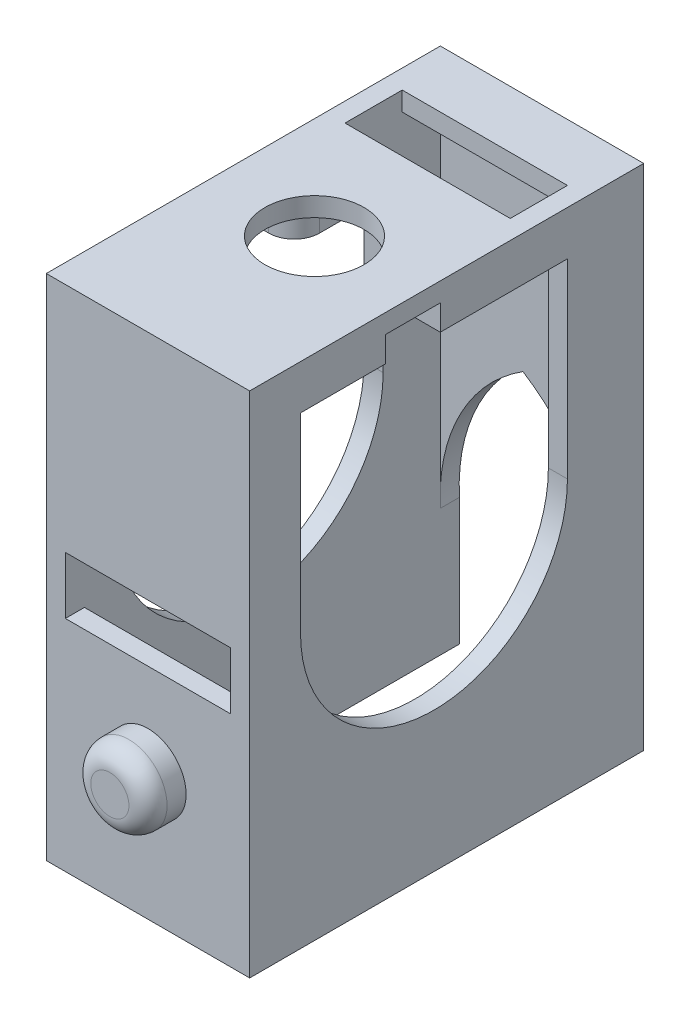
SolidWorks part; units mm, degrees
ref_plane "Front Plane" through (0, 0, 0) normal (0, 0, 1) x (1, 0, 0)
ref_plane "Top Plane" through (0, 0, 0) normal (0, 1, 0) x (1, 0, 0)
ref_plane "Right Plane" through (0, 0, 0) normal (1, 0, 0) x (0, 0, -1)
sketch "Sketch1" plane through (0, 0, 0) normal (0, 1, 0) x (1, 0, 0)
  line L1 (0, 0) -> (16, 0)
  line L2 (0, 0) -> (0, -31)
  line L3 (0, -31) -> (16, -31)
  line L4 (16, 0) -> (16, -31)
  dimension "D1" = 16
  dimension "D2" = 31
extrude "Boss-Extrude1" add sketch "Sketch1" along normal blind 40
shell "Shell1" thickness 1.5
sketch "Sketch2" plane through (0, 40, 0) normal (0, 1, 0) x (1, 0, 0)
  line L0 (16, 0) -> (0, 0) construction
  line L1 (1.5, -4.5) -> (14.5, -4.5)
  line L2 (1.5, -4.5) -> (1.5, -9)
  line L3 (1.5, -9) -> (14.5, -9)
  line L4 (14.5, -4.5) -> (14.5, -9)
  line L5 (16, -31) -> (16, 0) construction
  dimension "D1" = 13
  dimension "D2" = 4.5
  dimension "D3" = 4.5
  dimension "D4" = 1.5
extrude "Cut-Extrude1" cut sketch "Sketch2" against normal up to vertex (1.5 mm away)
sketch "Sketch3" plane through (0, 0, 0) normal (0, 0, -1) x (-1, 0, 0)
  line L0 (-16, 0) -> (0, 0) construction
  line L2 (-14.5, 10) -> (-14.5, -1)
  line L3 (-14.5, -1) -> (-1.5, -1)
  line L4 (-1.5, 10) -> (-1.5, -1)
  line L5 (-8, 10) -> (-8, 23.3795) construction
  line L6 (0, 40) -> (0, 0) construction
  arc A0 (-14.5, 10) -> (-8, 22.5665) centre (-0.5119, 10.729) cw
  arc A1 (-1.5, 10) -> (-8, 22.5665) centre (-15.4881, 10.729) ccw
  dimension "D4" = 1.5
  dimension "D1" = 13
  dimension "D2" = 1
  dimension "D3" = 11
extrude "Cut-Extrude2" cut sketch "Sketch3" against normal up to vertex (1.5 mm away)
sketch "Sketch4" plane through (0, 40, 0) normal (0, 1, 0) x (1, 0, 0)
  line L0 (1.5, -9) -> (14.5, -9) construction
  line L1 (16, -31) -> (16, 0) construction
  circle A0 centre (8, -17.9) radius 3.9
  dimension "D1" = 7.8
  dimension "D2" = 8.9
  dimension "D3" = 8
extrude "Cut-Extrude3" cut sketch "Sketch4" against normal up to vertex (1.5 mm away)
sketch "Sketch6" plane through (0, 38.5, 0) normal (0, -1, 0) x (-1, 0, 0)
  line L1 (-11.5, -9) -> (-14.5, -9)
  line L2 (-11.5, -9) -> (-11.5, -16)
  line L3 (-11.5, -16) -> (-14.5, -16)
  line L4 (-14.5, -9) -> (-14.5, -16)
  line L6 (-8, -9) -> (-8, -6.5435) construction
  line L7 (-1.5, -9) -> (-14.5, -9) construction
  line L8 (-4.5, -16) -> (-1.5, -16)
  line L9 (-1.5, -9) -> (-1.5, -16)
  line L10 (-4.5, -9) -> (-1.5, -9)
  line L11 (-4.5, -9) -> (-4.5, -16)
  dimension "D1" = 3
  dimension "D2" = 7
extrude "Boss-Extrude2" add sketch "Sketch6" along normal blind 2
sketch "Sketch7" plane through (0, 38.5, 0) normal (0, -1, 0) x (-1, 0, 0)
  line L0 (-8, -29.5) -> (-8, -32.4135) construction
  line L1 (-11.3, -20.3) -> (-14.5, -20.3)
  line L2 (-11.3, -20.3) -> (-11.3, -29.5)
  line L3 (-11.3, -29.5) -> (-14.5, -29.5)
  line L4 (-14.5, -20.3) -> (-14.5, -29.5)
  line L5 (-1.5, -29.5) -> (-14.5, -29.5) construction
  line L6 (-4.7, -29.5) -> (-1.5, -29.5)
  line L7 (-1.5, -20.3) -> (-1.5, -29.5)
  line L8 (-4.7, -20.3) -> (-1.5, -20.3)
  line L9 (-4.7, -20.3) -> (-4.7, -29.5)
  dimension "D1" = 3.2
  dimension "D2" = 9.2
extrude "Boss-Extrude3" add sketch "Sketch7" along normal blind 2
sketch "Sketch9" plane through (0, 0, 31) normal (0, 0, 1) x (1, 0, 0)
  line L1 (1.5, 21.7471) -> (14.5, 21.7471)
  line L2 (1.5, 21.7471) -> (1.5, 17.2471)
  line L3 (1.5, 17.2471) -> (14.5, 17.2471)
  line L4 (14.5, 21.7471) -> (14.5, 17.2471)
  line L6 (16, 40) -> (16, 0) construction
  dimension "D1" = 13
  dimension "D2" = 1.5
  dimension "D3" = 4.5
extrude "Cut-Extrude5" cut sketch "Sketch9" against normal up to vertex (1.5 mm away)
fillet "Fillet1" radius 2 4 edges at (11.3, 37.5, 20.3) (4.7, 37.5, 20.3) (11.5, 37.5, 16) (4.5, 37.5, 16)
sketch "Sketch10" plane through (0, 0, 31) normal (0, 0, 1) x (1, 0, 0)
  line L0 (0, 0) -> (16, 0) construction
  line L1 (16, 40) -> (16, 0) construction
  circle A0 centre (8, 10) radius 3
  dimension "D1" = 6
  dimension "D2" = 10
  dimension "D3" = 8
extrude "Boss-Extrude4" add sketch "Sketch10" along normal blind 3
fillet "Fillet2" radius 1.5 1 edges at (11, 10, 34)
sketch "Sketch11" plane through (0, 0, 0) normal (-1, 0, 0) x (0, 0, 1)
  line L0 (31, 40) -> (31, 0) construction
  line L1 (6, 36.5) -> (27, 36.5)
  line L2 (6, 36.5) -> (6, 21.5)
  line L4 (27, 36.5) -> (27, 21.5)
  line L5 (31, 40) -> (0, 40) construction
  arc A0 (6, 21.5) -> (27, 21.5) centre (16.5, 21.5) ccw
  dimension "D4" = 3.5
  dimension "D1" = 21
  dimension "D2" = 15
  dimension "D3" = 4
extrude "Cut-Extrude6" cut sketch "Sketch11" against normal through all
sketch "Sketch12" plane through (16, 0, 0) normal (1, 0, 0) x (0, 0, -1)
  line L1 (-16, 36.5) -> (-20.3, 36.5)
  line L2 (-16, 36.5) -> (-16, 38.5)
  line L3 (-16, 38.5) -> (-20.3, 38.5)
  line L4 (-20.3, 36.5) -> (-20.3, 38.5)
extrude "Cut-Extrude7" cut sketch "Sketch12" against normal through all
